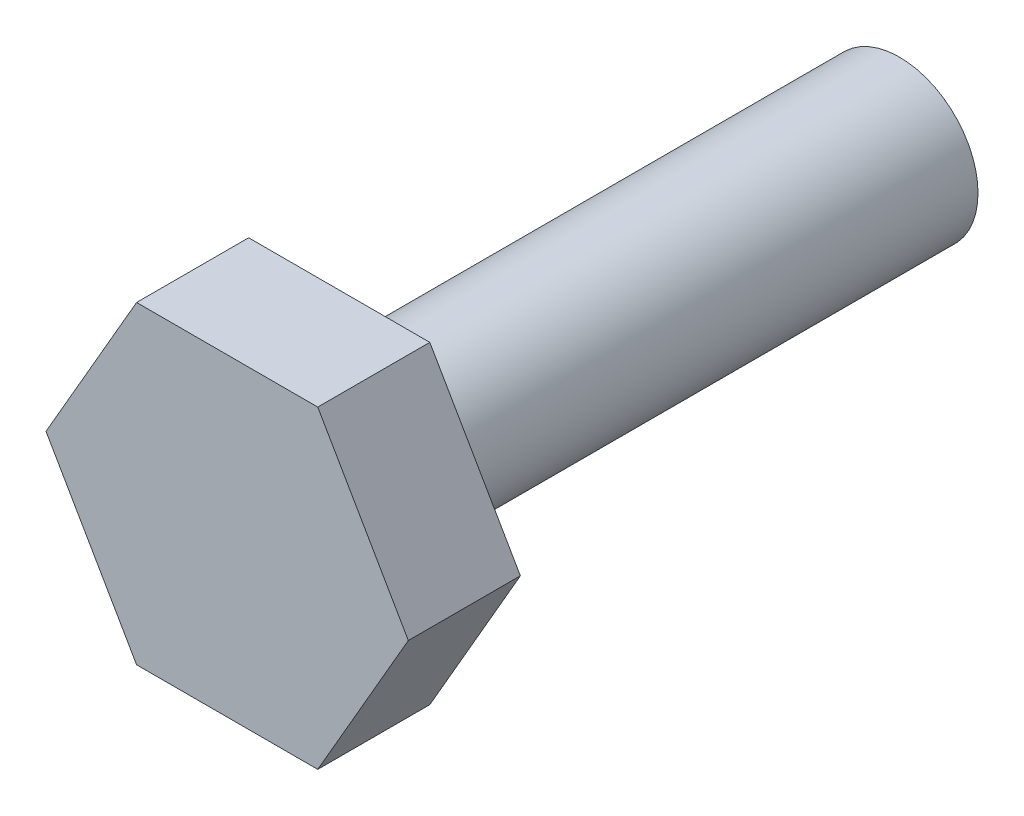
SolidWorks part; units mm, degrees
material "Plain Carbon Steel"
ref_plane "Front Plane" through (0, 0, 0) normal (0, 0, 1) x (1, 0, 0)
ref_plane "Top Plane" through (0, 0, 0) normal (0, 1, 0) x (1, 0, 0)
ref_plane "Right Plane" through (0, 0, 0) normal (1, 0, 0) x (0, 0, -1)
sketch "Sketch1" plane through (0, 0, 0) normal (0, 0, 1) x (1, 0, 0)
  line L0 (4.0415, 0) -> (2.0207, 3.5)
  line L1 (2.0207, 3.5) -> (-2.0207, 3.5)
  line L2 (-2.0207, 3.5) -> (-4.0415, 0)
  line L3 (-4.0415, 0) -> (-2.0207, -3.5)
  line L4 (-2.0207, -3.5) -> (2.0207, -3.5)
  line L5 (2.0207, -3.5) -> (4.0415, 0)
  dimension "D1" = 4.0415
  dimension "D2" = 2.0207
  dimension "D3" = 3.5
  dimension "D4" = 4.0415
  dimension "D5" = 2.0207
  dimension "D6" = 3.5
  dimension "D7" = 2.0207
  dimension "D8" = 3.5
  dimension "D9" = 4.0415
extrude "Boss-Extrude1" add sketch "Sketch1" along normal blind 2.5 from offset 0
sketch "Sketch2" plane through (0, 0, 0) normal (0, 0, 1) x (1, 0, 0)
  circle A0 centre (0, 0) radius 1.75
  dimension "D1" = 3.5
extrude "Boss-Extrude2" add sketch "Sketch2" along normal blind 12.5 from offset 12.5
